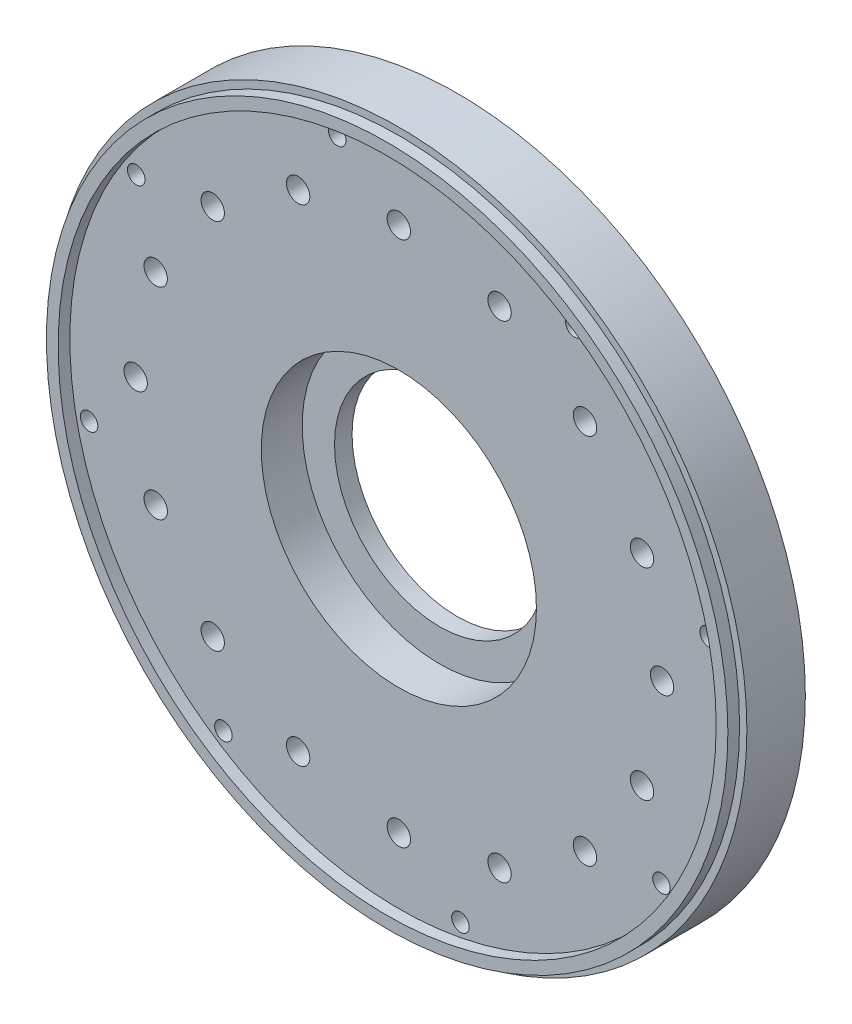
SolidWorks part; units mm, degrees
ref_plane "Front Plane" through (0, 0, 0) normal (0, 0, 1) x (1, 0, 0)
ref_plane "Top Plane" through (0, 0, 0) normal (0, 1, 0) x (1, 0, 0)
ref_plane "Right Plane" through (0, 0, 0) normal (1, 0, 0) x (0, 0, -1)
sketch "Sketch1" plane through (0, 0, 0) normal (0, 0, 1) x (1, 0, 0)
  circle A0 centre (0, 0) radius 59.5
  dimension "D1" = 119
extrude "Boss-Extrude1" add sketch "Sketch1" along normal blind 10
sketch "Sketch2" plane through (0, 0, 10) normal (0, 0, 1) x (1, 0, 0)
  line L0 (0, 0) -> (75.392, 0) construction
  circle A0 centre (0, 0) radius 45 construction
  arc A1 (45.2311, -8.997) -> (45.2311, 8.997) centre (45, 0) ccw
  arc A2 (38.3451, -25.6214) -> (45.2311, -8.997) centre (41.5746, -17.2208) ccw
  arc A3 (25.6214, -38.3451) -> (38.3451, -25.6214) centre (31.8198, -31.8198) ccw
  arc A4 (8.997, -45.2311) -> (25.6214, -38.3451) centre (17.2208, -41.5746) ccw
  arc A5 (-8.997, -45.2311) -> (8.997, -45.2311) centre (0, -45) ccw
  arc A6 (-25.6214, -38.3451) -> (-8.997, -45.2311) centre (-17.2208, -41.5746) ccw
  arc A7 (-38.3451, -25.6214) -> (-25.6214, -38.3451) centre (-31.8198, -31.8198) ccw
  arc A8 (-45.2311, -8.997) -> (-38.3451, -25.6214) centre (-41.5746, -17.2208) ccw
  arc A9 (-45.2311, 8.997) -> (-45.2311, -8.997) centre (-45, 0) ccw
  arc A10 (-38.3451, 25.6214) -> (-45.2311, 8.997) centre (-41.5746, 17.2208) ccw
  arc A11 (-25.6214, 38.3451) -> (-38.3451, 25.6214) centre (-31.8198, 31.8198) ccw
  arc A12 (-8.997, 45.2311) -> (-25.6214, 38.3451) centre (-17.2208, 41.5746) ccw
  arc A13 (8.997, 45.2311) -> (-8.997, 45.2311) centre (0, 45) ccw
  arc A14 (25.6214, 38.3451) -> (8.997, 45.2311) centre (17.2208, 41.5746) ccw
  arc A15 (38.3451, 25.6214) -> (25.6214, 38.3451) centre (31.8198, 31.8198) ccw
  arc A16 (45.2311, 8.997) -> (38.3451, 25.6214) centre (41.5746, 17.2208) ccw
  circle A17 centre (0, 0) radius 59.5
  point P38 (0, 0)
  dimension "D1" = 90
  dimension "D2" = 18
  dimension "D3" = 16
sketch "Sketch4" plane through (0, 0, 10) normal (0, 0, 1) x (1, 0, 0)
  circle A0 centre (0, 0) radius 23.525
  dimension "D1" = 47.05
extrude "Cut-Extrude2" cut sketch "Sketch4" against normal blind 7
sketch "Sketch5" plane through (0, 0, 3) normal (0, 0, 1) x (1, 0, 0)
  circle A0 centre (0, 0) radius 18
  dimension "D1" = 36
extrude "Cut-Extrude3" cut sketch "Sketch5" against normal through all
sketch "Sketch7" plane through (0, 0, 10) normal (0, 0, 1) x (1, 0, 0)
  line L0 (0, 0) -> (45, 0) construction
  line L1 (0, 0) -> (41.5746, -17.2208) construction
  circle A0 centre (45, 0) radius 2
  circle A1 centre (41.5746, -17.2208) radius 2
  circle A2 centre (31.8198, -31.8198) radius 2
  circle A3 centre (17.2208, -41.5746) radius 2
  circle A4 centre (0, -45) radius 2
  circle A5 centre (-17.2208, -41.5746) radius 2
  circle A6 centre (-31.8198, -31.8198) radius 2
  circle A7 centre (-41.5746, -17.2208) radius 2
  circle A8 centre (-45, 0) radius 2
  circle A9 centre (-41.5746, 17.2208) radius 2
  circle A10 centre (-31.8198, 31.8198) radius 2
  circle A11 centre (-17.2208, 41.5746) radius 2
  circle A12 centre (0, 45) radius 2
  circle A13 centre (17.2208, 41.5746) radius 2
  circle A14 centre (31.8198, 31.8198) radius 2
  circle A15 centre (41.5746, 17.2208) radius 2
  dimension "D1" = 4
  dimension "D3" = 22.5
  dimension "D2" = 16
extrude "Cut-Extrude4" cut sketch "Sketch7" against normal blind 4
sketch "Sketch8" plane through (0, 0, 10) normal (0, 0, 1) x (1, 0, 0)
  line L0 (0, 0) -> (42.6822, 63.8784) construction
  circle A0 centre (0, 0) radius 54 construction
  circle A1 centre (30.0008, 44.8994) radius 1.5
  circle A2 centre (52.9624, 10.5349) radius 1.5
  circle A3 centre (44.8994, -30.0008) radius 1.5
  circle A4 centre (10.5349, -52.9624) radius 1.5
  circle A5 centre (-30.0008, -44.8994) radius 1.5
  circle A6 centre (-52.9624, -10.5349) radius 1.5
  circle A7 centre (-44.8994, 30.0008) radius 1.5
  circle A8 centre (-10.5349, 52.9624) radius 1.5
  point P22 (0, 0)
  dimension "D1" = 3
  dimension "D3" = 108
  dimension "D2" = 8
extrude "Cut-Extrude5" cut sketch "Sketch8" against normal through all
sketch "Sketch10" plane through (0, 0, 10) normal (0, 0, 1) x (1, 0, 0)
  circle A0 centre (0, 0) radius 57.25
  circle A1 centre (0, 0) radius 59.5 construction
  circle A2 centre (0, 0) radius 58.25
  circle A3 centre (0, 0) radius 56.25
  dimension "D1" = 2.25
  dimension "D2" = 1
  dimension "D3" = 1
extrude "Boss-Extrude2" add sketch "Sketch10" along normal blind 2 contours A2 A0 | A0 A3
